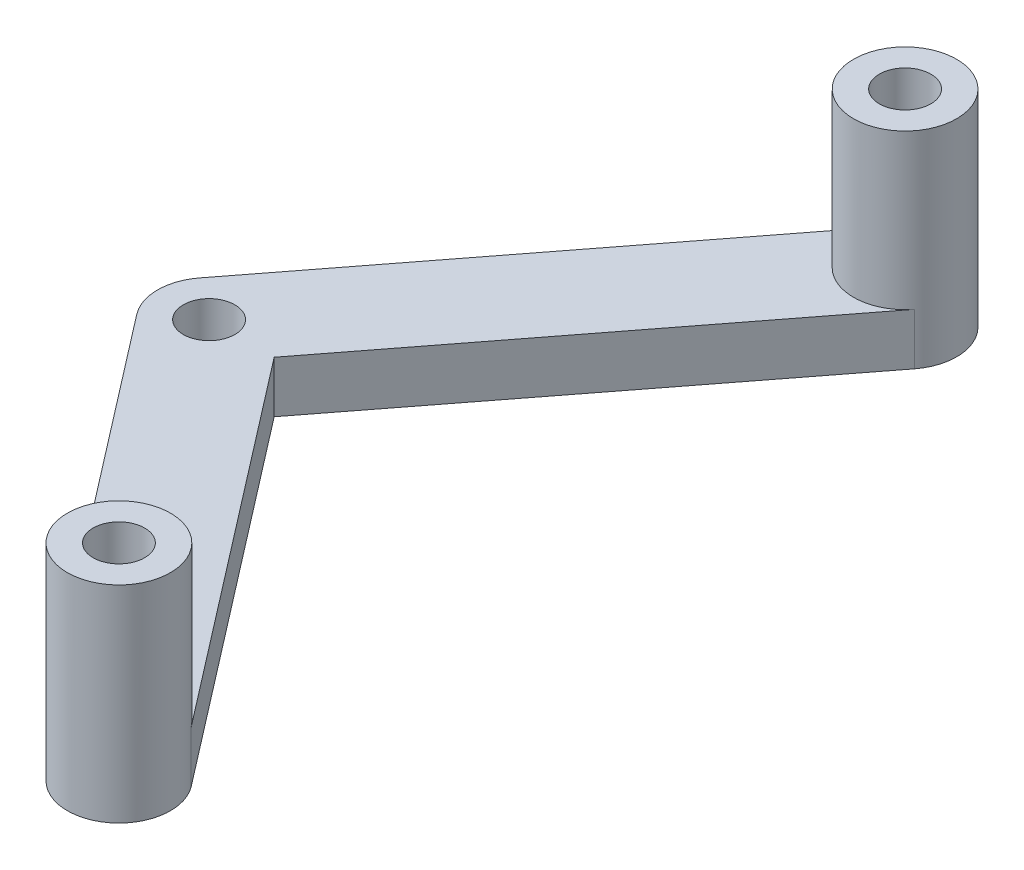
SolidWorks part; units mm, degrees
ref_plane "Front Plane" through (0, 0, 0) normal (0, 0, 1) x (1, 0, 0)
ref_plane "Top Plane" through (0, 0, 0) normal (0, 1, 0) x (1, 0, 0)
ref_plane "Right Plane" through (0, 0, 0) normal (1, 0, 0) x (0, 0, -1)
sketch "Sketch1" plane through (0, 0, 0) normal (0, 1, 0) x (1, 0, 0)
  line L0 (11.75, 15.248) -> (0, 0) construction
  line L1 (10.1658, 16.4687) -> (13.3342, 14.0272) construction
  line L2 (10.1658, 16.4687) -> (-1.5842, 1.2208)
  line L3 (-1.5842, 1.2208) -> (1.5842, -1.2208) construction
  line L4 (13.3342, 14.0272) -> (2.5249, 0)
  line L5 (0, 0) -> (1, 0) construction
  line L6 (10.1658, -16.4687) -> (13.3342, -14.0272) construction
  line L7 (11.75, -15.248) -> (0, 0) construction
  line L8 (13.3342, -14.0272) -> (2.5249, 0)
  line L9 (10.1658, -16.4687) -> (-1.5842, -1.2208)
  line L10 (2.5249, 0) -> (11.2097, 0) construction
  circle A0 centre (0, 0) radius 1
  arc A2 (13.3342, 14.0272) -> (10.1658, 16.4687) centre (11.75, 15.248) ccw
  circle A3 centre (11.75, 15.248) radius 1
  arc A4 (-1.5842, -1.2208) -> (-1.5842, 1.2208) centre (0, 0) cw
  circle A5 centre (11.75, -15.248) radius 1
  arc A6 (13.3342, -14.0272) -> (10.1658, -16.4687) centre (11.75, -15.248) cw
  point P2 (11.75, 15.248)
  point P10 (0, 0)
  point P19 (11.75, -15.248)
  dimension "D1" = 11.75
  dimension "D2" = 2
  dimension "D3" = 2
  dimension "D4" = 4
  dimension "D5" = 19.25
  dimension "D6" = 17.7088
extrude "Boss-Extrude1" add sketch "Sketch1" along normal blind 2
sketch "Sketch3" plane through (0, 2, 0) normal (0, 1, 0) x (1, 0, 0)
  circle A0 centre (11.75, 15.248) radius 1
  circle A1 centre (11.75, 15.248) radius 2
  circle A2 centre (11.75, -15.248) radius 1
  circle A3 centre (11.75, -15.248) radius 2
  dimension "D1" = 2
  dimension "D2" = 4
extrude "Boss-Extrude3" add sketch "Sketch3" along normal blind 6
